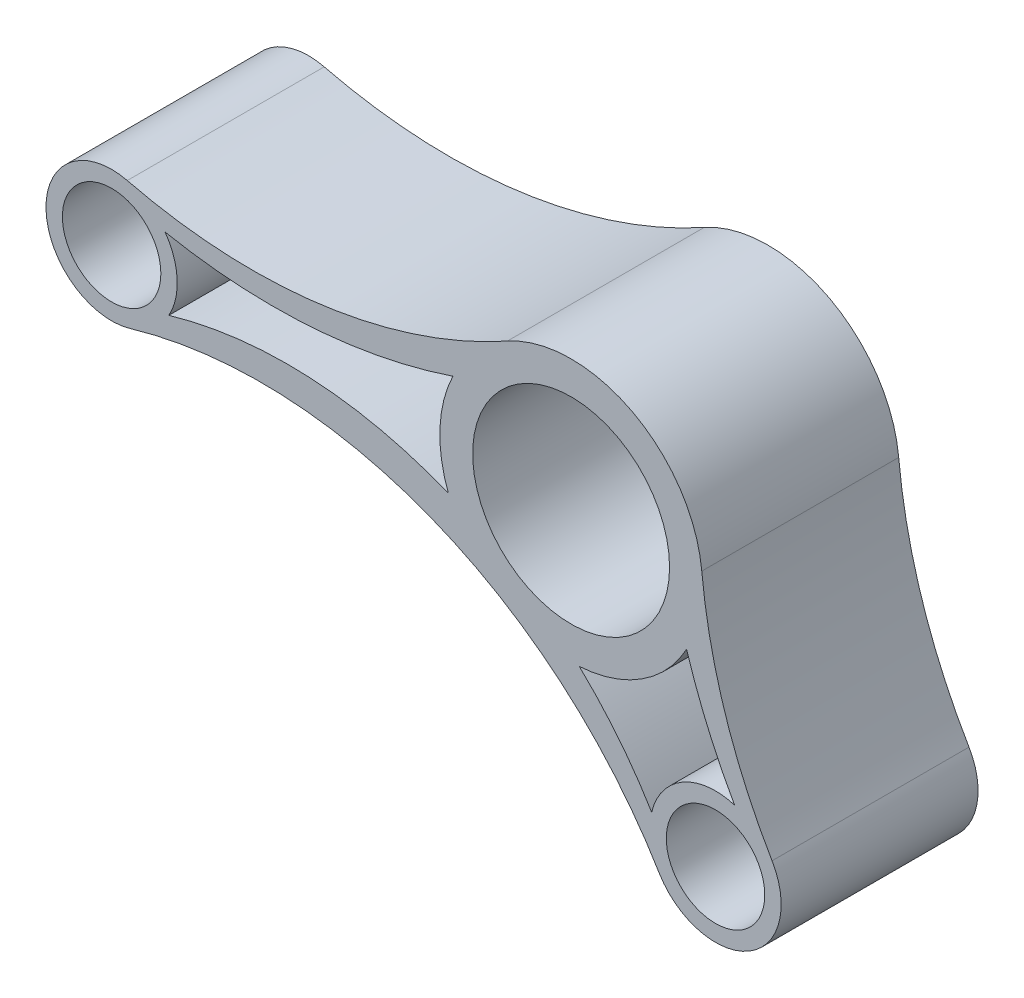
SolidWorks part; units mm, degrees
ref_plane "Front Plane" through (0, 0, 0) normal (0, 0, 1) x (1, 0, 0)
ref_plane "Top Plane" through (0, 0, 0) normal (0, 1, 0) x (1, 0, 0)
ref_plane "Right Plane" through (0, 0, 0) normal (1, 0, 0) x (0, 0, -1)
sketch "Sketch1" plane through (0, 0, 0) normal (0, 0, 1) x (1, 0, 0)
  line L0 (-70, 0) -> (-62.5, 0) construction
  line L1 (0, 31.6162) -> (0, 17.1834) construction
  line L2 (0, 15) -> (0, -15) construction
  line L3 (-60, 0) -> (-20, 0) construction
  line L4 (-15, 0) -> (31.7689, 0) construction
  line L5 (0, -20) -> (0, -42.2058) construction
  circle A0 centre (0, 0) radius 20
  circle A1 centre (0, 0) radius 15
  circle A2 centre (-70, 0) radius 7.5
  circle A3 centre (-70, 0) radius 10
  circle A4 centre (22, -36) radius 10
  circle A5 centre (22, -36) radius 7.5
  arc A7 (-67.619, 9.7124) -> (-9.7143, 17.4824) centre (-48.5714, 87.4118) ccw
  arc A9 (13.4165, -41.1306) -> (-67.1781, -9.5936) centre (-47.2376, -77.385) ccw
  arc A10 (19.9055, 1.9422) -> (30.6142, -30.921) centre (99.5274, 9.7112) ccw
  arc A12 (-61.8506, 5.7954) -> (-18.0106, 8.6959) centre (-45.4196, 90.2112) ccw
  arc A14 (12.27, -33.692) -> (1.2469, -19.9611) centre (-43.1236, -66.8714) ccw
  arc A15 (14.8115, 2.3709) -> (15.2251, 0) centre (99.7304, 15.9637) ccw
  arc A16 (-18.6975, -7.0994) -> (-61.2876, -4.9086) centre (-43.1236, -66.8714) ccw
  arc A17 (17.5914, -9.5153) -> (24.9065, -26.4317) centre (99.7304, 15.9637) ccw
  dimension "D1" = 40
  dimension "D2" = 30
  dimension "D3" = 15
  dimension "D4" = 20
  dimension "D5" = 70
  dimension "D6" = 22
  dimension "D7" = 36
extrude "Boss-Extrude1" add sketch "Sketch1" along normal mid plane 30
